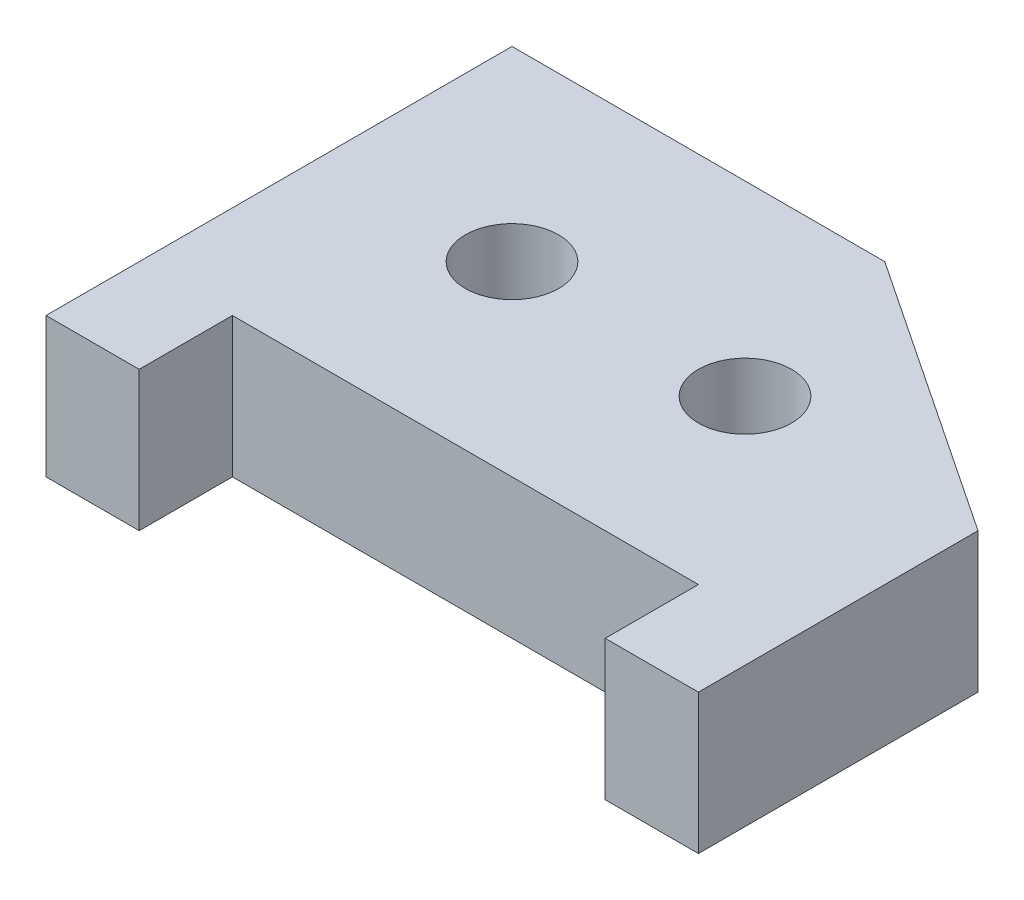
SolidWorks part; units mm, degrees
ref_plane "Front Plane" through (0, 0, 0) normal (0, 0, 1) x (1, 0, 0)
ref_plane "Top Plane" through (0, 0, 0) normal (0, 1, 0) x (1, 0, 0)
ref_plane "Right Plane" through (0, 0, 0) normal (1, 0, 0) x (0, 0, -1)
sketch "Sketch1" plane through (0, 0, 0) normal (0, 1, 0) x (1, 0, 0)
  line L0 (-88.9, 0) -> (-76.2, 0)
  line L1 (-76.2, 0) -> (-76.2, 12.7)
  line L2 (-76.2, 12.7) -> (-12.7, 12.7)
  line L3 (-12.7, 12.7) -> (-12.7, 0)
  line L4 (-12.7, 0) -> (0, 0)
  line L5 (0, 0) -> (0, 38.1)
  line L6 (0, 38.1) -> (-38.1, 63.5)
  line L7 (-38.1, 63.5) -> (-88.9, 63.5)
  line L8 (-88.9, 63.5) -> (-88.9, 0)
  circle A0 centre (-63.5, 38.1) radius 6.35
  circle A1 centre (-31.75, 38.1) radius 6.35
  point P14 (0, 0)
  point P15 (0, 0)
  point P16 (0, 0)
  point P17 (0, 0)
  dimension "D4" = 31.75
  dimension "D8" = 12.7
  dimension "D12" = 25.4
  dimension "D1" = 12.7
  dimension "D2" = 12.7
  dimension "D3" = 50.8
  dimension "D5" = 63.5
  dimension "D6" = 88.9
  dimension "D7" = 25.4
  dimension "D9" = 38.1
  dimension "D10" = 63.5
  dimension "D11" = 25.4
extrude "Boss-Extrude1" add sketch "Sketch1" along normal blind 19.05
